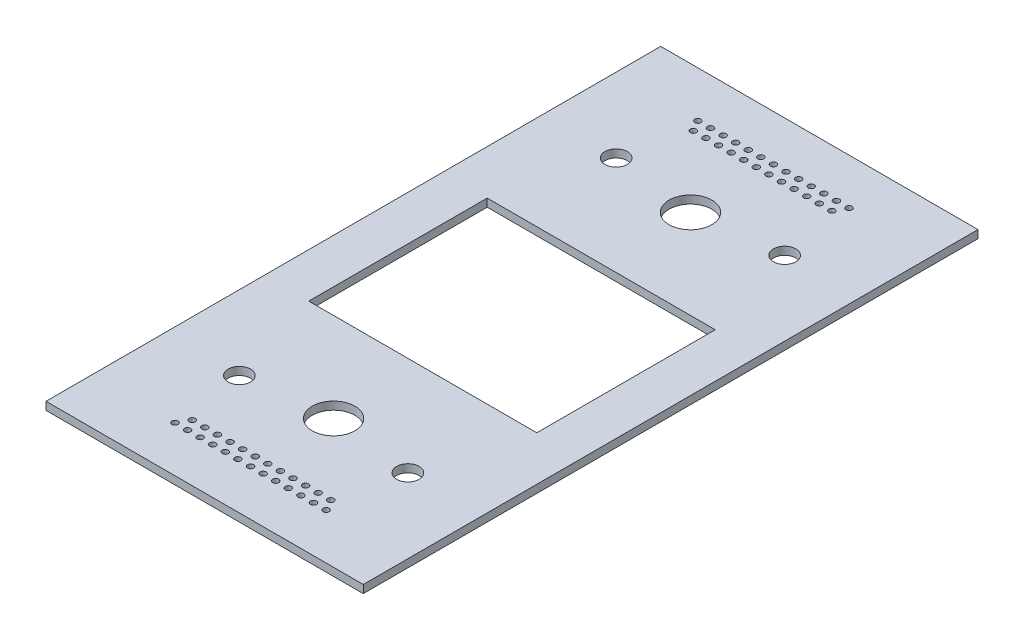
SolidWorks part; units mm, degrees
ref_plane "Front Plane" through (0, 0, 0) normal (0, 0, 1) x (1, 0, 0)
ref_plane "Top Plane" through (0, 0, 0) normal (0, 1, 0) x (1, 0, 0)
ref_plane "Right Plane" through (0, 0, 0) normal (1, 0, 0) x (0, 0, -1)
sketch "Sketch2" plane through (0, 0, 0) normal (0, 1, 0) x (1, 0, 0)
  line L0 (0, -31) -> (32, -31) construction
  line L1 (0, 0) -> (32, 0)
  line L2 (0, 0) -> (0, -62)
  line L3 (0, -62) -> (32, -62)
  line L4 (32, 0) -> (32, -62)
  line L5 (0, 0) -> (32, 0)
  line L6 (4.5, -40) -> (4.5, -22)
  line L7 (4.5, -22) -> (27.5, -22)
  line L8 (27.5, -22) -> (27.5, -40)
  line L9 (0, -62) -> (32, -62)
  line L10 (4.5, -40) -> (27.5, -40)
  circle A1 centre (9.02, -5.73) radius 0.305
  circle A2 centre (16, -13) radius 2.1527
  circle A3 centre (24.5, -12) radius 1.1303
  circle A4 centre (7.5, -12) radius 1.1303
  circle A5 centre (8.38, -4.63) radius 0.305
  circle A54 centre (7.5, -50) radius 1.1303
  circle A55 centre (24.5, -50) radius 1.1303
  circle A56 centre (16, -49) radius 2.1527
  circle A57 centre (9.65, -4.63) radius 0.305
  circle A58 centre (10.92, -4.63) radius 0.305
  circle A59 centre (12.19, -4.63) radius 0.305
  circle A60 centre (13.46, -4.63) radius 0.305
  circle A61 centre (14.73, -4.63) radius 0.305
  circle A62 centre (16, -4.63) radius 0.305
  circle A63 centre (17.27, -4.63) radius 0.305
  circle A64 centre (18.54, -4.63) radius 0.305
  circle A65 centre (19.81, -4.63) radius 0.305
  circle A66 centre (21.08, -4.63) radius 0.305
  circle A67 centre (22.35, -4.63) radius 0.305
  circle A68 centre (23.62, -4.63) radius 0.305
  circle A69 centre (10.29, -5.73) radius 0.305
  circle A70 centre (11.56, -5.73) radius 0.305
  circle A71 centre (12.83, -5.73) radius 0.305
  circle A72 centre (14.1, -5.73) radius 0.305
  circle A73 centre (15.37, -5.73) radius 0.305
  circle A74 centre (16.64, -5.73) radius 0.305
  circle A75 centre (17.91, -5.73) radius 0.305
  circle A76 centre (19.18, -5.73) radius 0.305
  circle A77 centre (20.45, -5.73) radius 0.305
  circle A78 centre (21.72, -5.73) radius 0.305
  circle A79 centre (22.99, -5.73) radius 0.305
  circle A80 centre (22.99, -56.27) radius 0.305
  circle A81 centre (21.72, -56.27) radius 0.305
  circle A82 centre (20.45, -56.27) radius 0.305
  circle A83 centre (19.18, -56.27) radius 0.305
  circle A84 centre (17.91, -56.27) radius 0.305
  circle A85 centre (16.64, -56.27) radius 0.305
  circle A86 centre (15.37, -56.27) radius 0.305
  circle A87 centre (14.1, -56.27) radius 0.305
  circle A88 centre (12.83, -56.27) radius 0.305
  circle A89 centre (11.56, -56.27) radius 0.305
  circle A90 centre (10.29, -56.27) radius 0.305
  circle A91 centre (23.62, -57.37) radius 0.305
  circle A92 centre (22.35, -57.37) radius 0.305
  circle A93 centre (21.08, -57.37) radius 0.305
  circle A94 centre (19.81, -57.37) radius 0.305
  circle A95 centre (18.54, -57.37) radius 0.305
  circle A96 centre (17.27, -57.37) radius 0.305
  circle A97 centre (16, -57.37) radius 0.305
  circle A98 centre (14.73, -57.37) radius 0.305
  circle A99 centre (13.46, -57.37) radius 0.305
  circle A100 centre (12.19, -57.37) radius 0.305
  circle A101 centre (10.92, -57.37) radius 0.305
  circle A102 centre (9.65, -57.37) radius 0.305
  circle A103 centre (8.38, -57.37) radius 0.305
  circle A104 centre (9.02, -56.27) radius 0.305
  point P8 (16, 0)
  point P125 (4.5, -31)
  point P126 (27.5, -31)
  dimension "D1" = 2.2606
  dimension "D2" = 4.3053
  dimension "D13" = 0.61
  dimension "D3" = 62
  dimension "D4" = 32
  dimension "D5" = 12
  dimension "D6" = 7.5
  dimension "D7" = 7.5
  dimension "D8" = 13
  dimension "D9" = 23
  dimension "D10" = 4.5
  dimension "D11" = 9
  dimension "D12" = 13
  dimension "D14" = 8.38
  dimension "D15" = 1.1
  dimension "D16" = 0.64
  dimension "D17" = 4.63
  dimension "D18" = 1.27
  dimension "D19" = 12
  dimension "D20" = 1.27
extrude "Boss-Extrude1" add sketch "Sketch2" along normal blind 0.8 contours L0 L2 L3 L4 L8 L10 L6 A103 A101 A99 A97 A95 A93 A91 A89 A87 A85 A83 A81 A56 A54 A55 A80 A82 A84 A86 A88 A90 | L2 L0 L6 L7 L8 L4 L1 A79 A78 A77 A76 A75 A74 A73 A72 A71 A70 A69 A68 A67 A66 A65 A64 A63 A62 A61 A60 A59
